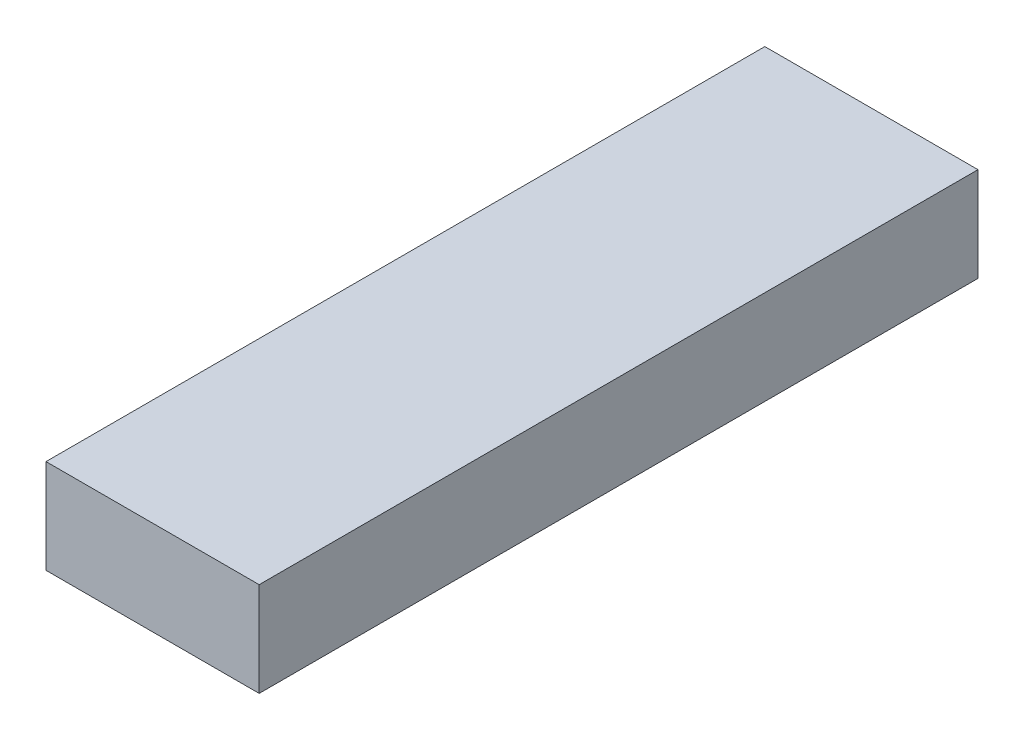
SolidWorks part; units mm, degrees
ref_plane "Plan de face" through (0, 0, 0) normal (0, 0, 1) x (1, 0, 0)
ref_plane "Plan de dessus" through (0, 0, 0) normal (0, 1, 0) x (1, 0, 0)
ref_plane "Plan de droite" through (0, 0, 0) normal (1, 0, 0) x (0, 0, -1)
sketch "Esquisse1" plane through (0, 0, 0) normal (0, 1, 0) x (1, 0, 0)
  line L1 (21.5, 72.5) -> (-21.5, 72.5)
  line L2 (21.5, 72.5) -> (21.5, -72.5)
  line L3 (21.5, -72.5) -> (-21.5, -72.5)
  line L4 (-21.5, 72.5) -> (-21.5, -72.5)
  line L5 (21.5, 72.5) -> (-21.5, -72.5) construction
  line L6 (21.5, -72.5) -> (-21.5, 72.5) construction
  point P0 (0, 0)
  dimension "D1" = 43
  dimension "D2" = 145
extrude "Boss.-Extru.1" add sketch "Esquisse1" along normal blind 19
